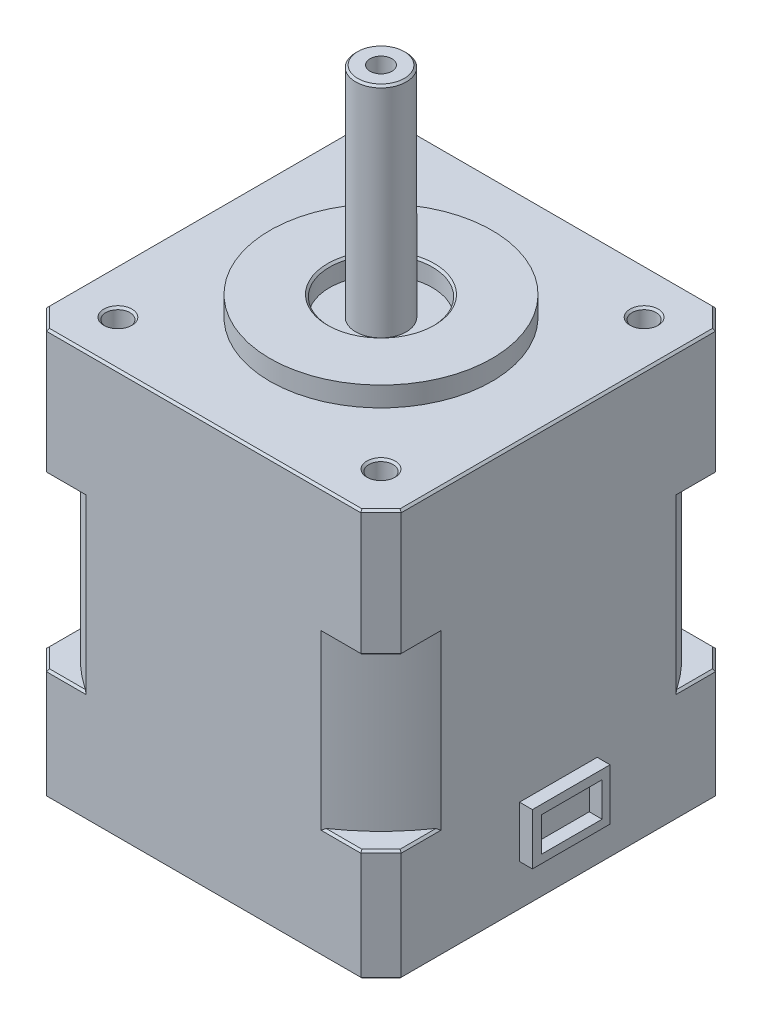
SolidWorks part; units mm, degrees
ref_plane "Front Plane" through (0, 0, 0) normal (0, 0, 1) x (1, 0, 0)
ref_plane "Top Plane" through (0, 0, 0) normal (0, 1, 0) x (1, 0, 0)
ref_plane "Right Plane" through (0, 0, 0) normal (1, 0, 0) x (0, 0, -1)
sketch "Sketch1" plane through (0, 0, 0) normal (1, 0, 0) x (0, 0, -1)
  line L0 (-35.052, 0) -> (0, 0)
  line L1 (0, 0) -> (0, 40.1574)
  line L2 (0, 40.1574) -> (-35.052, 40.1574)
  line L3 (-35.052, 40.1574) -> (-35.052, 0)
extrude "Boss-Extrude1" add sketch "Sketch1" against normal blind 35.052
ref_plane "Plane4" through (0, 27.7114, 0) normal (0, 1, 0) x (1, 0, 0)
sketch "Sketch2" plane through (0, 27.7114, 0) normal (0, 1, 0) x (1, 0, 0)
  line L0 (0, -5.9236) -> (0, 0)
  line L1 (0, 0) -> (-5.9236, 0)
  arc A0 (-5.9236, 0) -> (0, -5.9236) centre (-17.526, -17.526) cw
extrude "Cut-Extrude1" cut sketch "Sketch2" against normal blind 16.6878
sketch "Sketch3" plane through (0, 27.7114, 0) normal (0, 1, 0) x (1, 0, 0)
  line L0 (-29.1284, 0) -> (-35.052, 0)
  line L1 (-35.052, 0) -> (-35.052, -5.9236)
  arc A0 (-35.052, -5.9236) -> (-29.1284, 0) centre (-17.526, -17.526) cw
extrude "Cut-Extrude2" cut sketch "Sketch3" against normal blind 16.6878
sketch "Sketch4" plane through (0, 27.7114, 0) normal (0, 1, 0) x (1, 0, 0)
  line L0 (-35.052, -29.1284) -> (-35.052, -35.052)
  line L1 (-35.052, -35.052) -> (-29.1284, -35.052)
  arc A0 (-29.1284, -35.052) -> (-35.052, -29.1284) centre (-17.526, -17.526) cw
extrude "Cut-Extrude3" cut sketch "Sketch4" against normal blind 16.6878
ref_plane "Plane5" through (0, 11.0236, 0) normal (0, -1, 0) x (1, 0, 0)
sketch "Sketch5" plane through (0, 11.0236, 0) normal (0, -1, 0) x (1, 0, 0)
  line L0 (0, 29.1284) -> (0, 35.052)
  line L1 (0, 35.052) -> (-5.9236, 35.052)
  arc A0 (-5.9236, 35.052) -> (0, 29.1284) centre (-17.526, 17.526) cw
extrude "Cut-Extrude4" cut sketch "Sketch5" against normal blind 16.6878
sketch "Sketch6" plane through (0, 0, 0) normal (1, 0, 0) x (0, 0, -1)
  line L0 (-13.6906, 9.344) -> (-13.6906, 4.264)
  line L1 (-13.6906, 4.264) -> (-21.3614, 4.264)
  line L2 (-21.3614, 4.264) -> (-21.3614, 9.344)
  line L3 (-21.3614, 9.344) -> (-13.6906, 9.344)
extrude "Boss-Extrude2" add sketch "Sketch6" along normal blind 1.27
sketch "Sketch7" plane through (1.27, 0, 0) normal (1, 0, 0) x (0, 0, -1)
  line L0 (-14.4726, 8.455) -> (-20.4724, 8.455)
  line L1 (-20.4724, 8.455) -> (-20.4724, 5.0748)
  line L2 (-20.4724, 5.0748) -> (-14.4726, 5.0748)
  line L3 (-14.4726, 5.0748) -> (-14.4726, 8.455)
extrude "Cut-Extrude5" cut sketch "Sketch7" against normal blind 1.27
sketch "Sketch8" plane through (0, 40.1574, 0) normal (0, 1, 0) x (-1, 0, 0)
  circle A0 centre (17.526, 17.526) radius 10.9728
extrude "Boss-Extrude3" add sketch "Sketch8" along normal blind 1.9558
hole_wizard "Hole1" positions "Sketch10" profile "Sketch9" legacy
sketch "Sketch10" plane through (0, 42.1132, 0) normal (0, 1, 0) x (1, 0, 0)
  point P0 (-17.526, -17.526)
sketch "Sketch9" plane through (-17.526, 42.1132, 17.526) normal (1, 0, 0) x (0, 0, 1)
  line L0 (0, 0) -> (0, 1.9558)
  line L1 (0, 1.9558) -> (5.08, 1.9558)
  line L2 (5.08, 1.9558) -> (5.08, 0)
  line L3 (5.08, 0) -> (0, 0)
  line L4 (0, 110) -> (0, -10) construction
  dimension "Diameter" = 10.16
  dimension "Depth" = 1.9558
ref_plane "Plane6" through (0, 0, 17.526) normal (0, 0, -1) x (-1, 0, 0)
sketch "Sketch11" plane through (0, 0, 17.526) normal (0, 0, -1) x (-1, 0, 0)
  line L0 (15.026, 40.1574) -> (17.526, 40.1574)
  line L1 (17.526, 40.1574) -> (17.526, 61.7474)
  line L2 (17.526, 61.7474) -> (15.026, 61.7474)
  line L3 (15.026, 61.7474) -> (15.026, 40.1574)
  line L4 (17.526, 40.1574) -> (17.526, 61.7474) construction
revolve "Revolve1" add sketch "Sketch11" angle 360 about L4
hole_wizard "M8 Clearance Hole1" positions "Sketch13" profile "Sketch12" hole size "M8" standard "ANSI Metric"
sketch "Sketch13" plane through (0, 0, 0) normal (0, -1, 0) x (-1, 0, 0)
  point P0 (17.526, -17.526)
sketch "Sketch12" plane through (-17.526, 0, 17.526) normal (1, 0, 0) x (0, 0, -1)
  line L0 (0, 0) -> (0, 1.27)
  line L1 (0, 1.27) -> (4.699, 1.27)
  line L2 (4.699, 1.27) -> (4.699, 0)
  line L5 (4.699, 0) -> (0, 0)
  line L10 (0, 1.27) -> (-4.699, 1.27) construction
  line L11 (0, -6.35) -> (0, 107.95) construction
  dimension "Hole Dia." = 9.398
  dimension "Hole Depth" = 1.27
  dimension "Drill Angle" = 180
hole_wizard "M2 Clearance Hole1" positions "Sketch15" profile "Sketch14" hole size "M2" standard "ANSI Metric"
sketch "Sketch15" plane through (0, 40.1574, 0) normal (0, 1, 0) x (1, 0, 0)
  point P0 (-4.5308, -30.5212)
  point P1 (-30.5308, -4.5212)
  point P2 (-30.5308, -30.5212)
  point P3 (-4.5308, -4.5212)
sketch "Sketch14" plane through (-4.5308, 40.1574, 30.5212) normal (1, 0, 0) x (0, 0, 1)
  line L0 (0, 0) -> (0, 7.62)
  line L1 (0, 7.62) -> (1.1938, 7.62)
  line L2 (1.1938, 7.62) -> (1.1938, 0)
  line L5 (1.1938, 0) -> (0, 0)
  line L10 (0, 7.62) -> (-1.1938, 7.62) construction
  line L11 (0, -6.35) -> (0, 107.95) construction
  dimension "Hole Dia." = 2.3876
  dimension "Hole Depth" = 7.62
  dimension "Drill Angle" = 180
hole_wizard "Hole2" positions "Sketch17" profile "Sketch16" legacy
sketch "Sketch17" plane through (0, 61.7474, 0) normal (0, 1, 0) x (1, 0, 0)
  point P0 (-17.526, -17.526)
sketch "Sketch16" plane through (-17.526, 61.7474, 17.526) normal (1, 0, 0) x (0, 0, 1)
  line L0 (0, 0) -> (0, 2.54)
  line L1 (0, 2.54) -> (1.0795, 2.54)
  line L2 (1.0795, 2.54) -> (1.0795, 0)
  line L3 (1.0795, 0) -> (0, 0)
  line L4 (0, 110) -> (0, -10) construction
  dimension "Diameter" = 2.1591
  dimension "Depth" = 2.54
chamfer "Chamfer1" distance 2 angle 45 8 edges at (-35.052, 33.9344, 35.052) (0, 5.5118, 35.052) (-35.052, 5.5118, 0) (0, 33.9344, 0) (0, 5.5118, 0) (-35.052, 33.9344, 0) (0, 33.9344, 35.052) (-35.052, 5.5118, 35.052)
chamfer "Chamfer2" distance 0.2 angle 45 46 edges at (-31.0902, 27.7114, 35.052) (-34.052, 27.7114, 34.052) (-35.052, 27.7114, 31.0902) (-35.052, 0, 17.526) (-34.052, 0, 1) (-34.052, 0, 34.052) (-17.526, 0, 0) (-17.526, 0, 35.052) (-1, 0, 1) (-1, 0, 34.052) (0, 0, 17.526) (0, 11.0236, 31.0902) (-1, 11.0236, 34.052) (-3.9618, 11.0236, 35.052) (-17.526, 42.1132, 22.606) (-31.0902, 11.0236, 0) (-35.052, 11.0236, 3.9618) (-34.052, 11.0236, 1) (-4.5308, 40.1574, 31.715) (-17.526, 40.1574, 0) (-34.052, 40.1574, 1) (-1, 40.1574, 1) (-35.052, 40.1574, 17.526) (0, 40.1574, 17.526) (-34.052, 40.1574, 34.052) (-1, 40.1574, 34.052) (-17.526, 40.1574, 35.052) (-30.5308, 40.1574, 5.715) (-30.5308, 40.1574, 31.715) (-4.5308, 40.1574, 5.715) (-3.9618, 27.7114, 0) (0, 27.7114, 3.9618) (-1, 27.7114, 1) (-35.052, 27.7114, 3.9618) (-31.0902, 27.7114, 0) (-34.052, 27.7114, 1) (0, 27.7114, 31.0902) (-3.9618, 27.7114, 35.052) (-1, 27.7114, 34.052) (-31.0902, 11.0236, 35.052) (-34.052, 11.0236, 34.052) (-35.052, 11.0236, 31.0902) (-3.9618, 11.0236, 0) (-1, 11.0236, 1) (0, 11.0236, 3.9618) (-17.526, 61.7474, 20.026)
